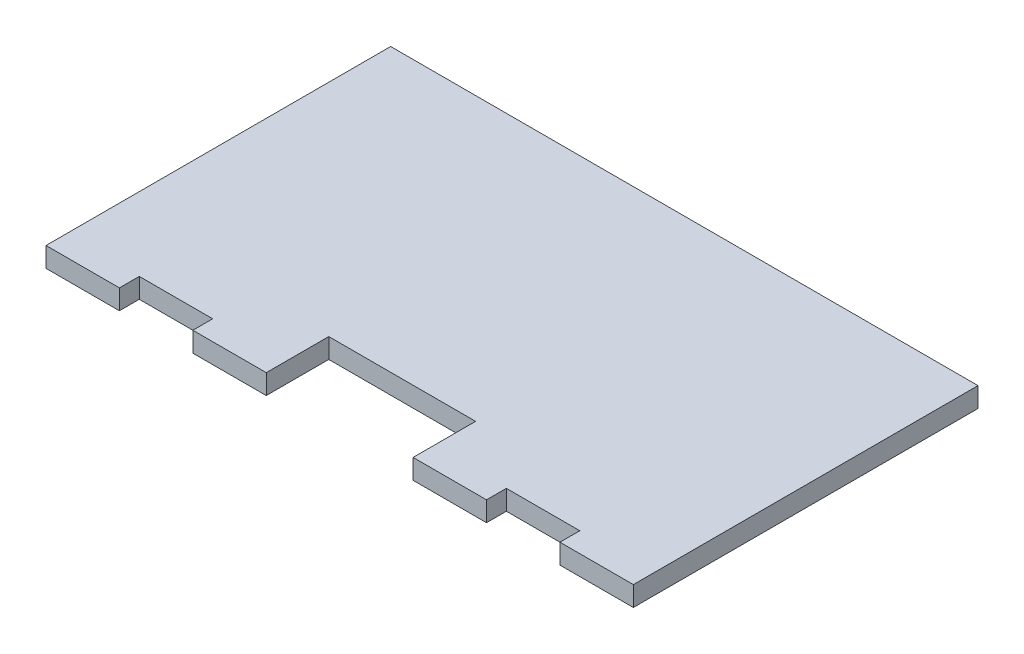
SolidWorks part; units mm, degrees
ref_plane "Front Plane" through (0, 0, 0) normal (0, 0, 1) x (1, 0, 0)
ref_plane "Top Plane" through (0, 0, 0) normal (0, 1, 0) x (1, 0, 0)
ref_plane "Right Plane" through (0, 0, 0) normal (1, 0, 0) x (0, 0, -1)
sketch "Sketch1" plane through (0, 0, 0) normal (0, 1, 0) x (1, 0, 0)
  line L1 (-189.329, 43.1681) -> (99.215, 43.1681)
  line L2 (-189.329, 43.1681) -> (-189.329, -126.1483)
  line L3 (-189.329, -126.1483) -> (99.215, -126.1483)
  line L4 (99.215, 43.1681) -> (99.215, -126.1483)
  dimension "D1" = 169.3164
  dimension "D2" = 288.544
extrude "Boss-Extrude1" add sketch "Sketch1" along normal blind 9.7536
sketch "Sketch2" plane through (0, 0, 0) normal (0, -1, 0) x (1, 0, 0)
  line L0 (-189.329, 126.1483) -> (99.215, 126.1483) construction
  line L1 (-153.261, 126.1483) -> (-117.193, 126.1483)
  line L2 (-153.261, 126.1483) -> (-153.261, 116.3947)
  line L3 (-153.261, 116.3947) -> (-117.193, 116.3947)
  line L4 (-117.193, 126.1483) -> (-117.193, 116.3947)
  line L5 (-45.057, 126.1483) -> (-45.057, -43.1681) construction
  line L6 (99.215, -43.1681) -> (-189.329, -43.1681) construction
  line L7 (-189.329, -43.1681) -> (-189.329, 126.1483) construction
  line L8 (-8.989, 126.1483) -> (-81.125, 126.1483)
  line L9 (-45.057, 126.1483) -> (-45.057, 95.4397)
  line L10 (-8.989, 95.4397) -> (-81.125, 95.4397)
  line L11 (-81.125, 126.1483) -> (-81.125, 95.4397)
  line L12 (-8.989, 126.1483) -> (-8.989, 95.4397)
  line L13 (63.147, 116.3947) -> (27.079, 116.3947)
  line L14 (27.079, 126.1483) -> (27.079, 116.3947)
  line L15 (63.147, 126.1483) -> (27.079, 126.1483)
  line L16 (63.147, 126.1483) -> (63.147, 116.3947)
  line M6 (99.215, 126.1483) -> (-189.329, 126.1483)
  dimension "D1" = 9.7536
  dimension "D2" = 30.7086
  dimension "D3" = 36.068
  dimension "D4" = 36.068
  dimension "D6" = 36.068
  dimension "D5" = 36.068
extrude "Cut-Extrude1" cut sketch "Sketch2" against normal through all contours L4 L2 L3 M6 | L8 L11 L10 L9 | L12 L9 L10 M6 | L16 L14 L13 M6
equation "\"D1@Sketch1\"=\"Side Height@Assembled Container.Assembly\""
equation "\"D2@Sketch1\"=\"Short Side Width@Assembled Container.Assembly\""
equation "\"D1@Boss-Extrude1\"=\"Acrylic Thickness@Assembled Container.Assembly\""
equation "\"D1@Sketch2\"=\"Acrylic Thickness@Assembled Container.Assembly\""
equation "\"D2@Sketch2\" = \"Short Side Finger Hole@Assembled Container.Assembly\""
equation "\"D3@Sketch2\"=\"Lid Short Side Outer Cutout@Assembled Container.Assembly\""
equation "\"D4@Sketch2\"=\"Lid Short Side Outer Overhang@Assembled Container.Assembly\""
equation "\"D5@Sketch2\"=\"Lid Short Side Middle Overhang@Assembled Container.Assembly\""
